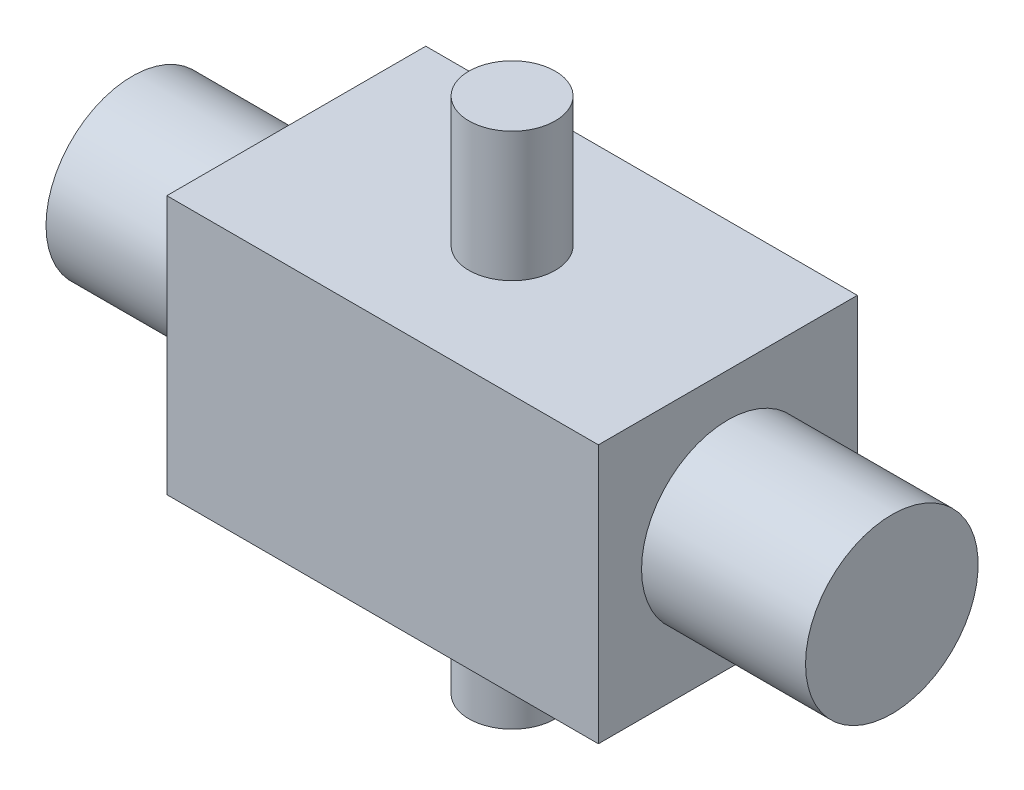
SolidWorks part; units mm, degrees
material "普通碳钢"
ref_plane "前视基准面" through (0, 0, 0) normal (0, 0, 1) x (1, 0, 0)
ref_plane "上视基准面" through (0, 0, 0) normal (0, 1, 0) x (1, 0, 0)
ref_plane "右视基准面" through (0, 0, 0) normal (1, 0, 0) x (0, 0, -1)
other "Configuration Table"
sketch "草图1" plane through (0, 0, 0) normal (0, 0, 1) x (1, 0, 0)
  line L1 (-44, 5) -> (44, 5)
  line L2 (-44, 5) -> (-44, -5)
  line L3 (-44, -5) -> (44, -5)
  line L4 (44, 5) -> (44, -5)
  line L5 (-44, 5) -> (44, -5) construction
  line L6 (-44, -5) -> (44, 5) construction
  point P0 (0, 0)
  dimension "D1" = 10
  dimension "D2" = 88
revolve "旋转1" add sketch "草图1" angle 360 about L3
sketch "草图3" plane through (0, 0, 0) normal (0, 0, 1) x (1, 0, 0)
  line L0 (44, -15) -> (44, 5) construction
  line L6 (0, -35) -> (5, -35)
  line L7 (0, -35) -> (0, 25)
  line L8 (0, 25) -> (5, 25)
  line L9 (5, -35) -> (5, 25)
  line L12 (-44, -5) -> (123.7035, -5) construction
  line L13 (-44, 5) -> (-44, -15) construction
  dimension "D1" = 5
  dimension "D2" = 60
  dimension "D3" = 30
  dimension "D4" = 44
revolve "旋转2" add sketch "草图3" angle 360 about L7
sketch "草图4" plane through (0, 0, 0) normal (1, 0, 0) x (0, 0, -1)
  line L1 (-15, 10) -> (15, 10)
  line L2 (-15, 10) -> (-15, -20)
  line L3 (-15, -20) -> (15, -20)
  line L4 (15, 10) -> (15, -20)
  line L5 (-15, 10) -> (15, -20) construction
  line L6 (-15, -20) -> (15, 10) construction
  point P0 (0, -5)
  dimension "D1" = 30
  dimension "D2" = 30
extrude "凸台-拉伸1" add sketch "草图4" along normal mid plane 50
